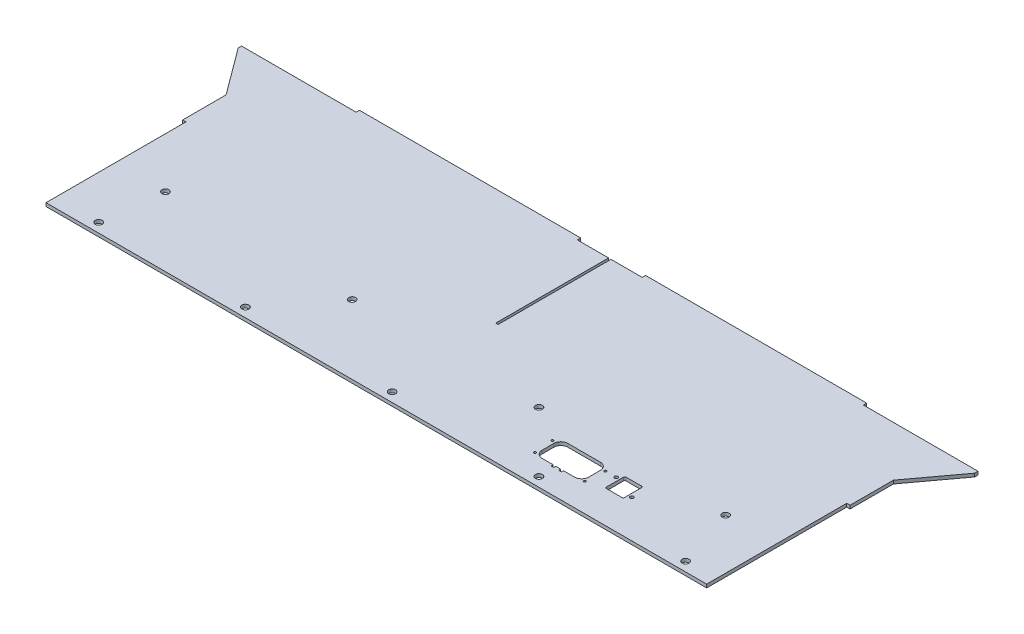
SolidWorks part; units mm, degrees
material "6061-T6 (SS)"
ref_plane "X-Y Datum" through (0, 0, 0) normal (0, 0, 1) x (1, 0, 0)
ref_plane "X-Z Datum" through (0, 0, 0) normal (0, 1, 0) x (1, 0, 0)
ref_plane "Y-Z Datum" through (0, 0, 0) normal (1, 0, 0) x (0, 0, -1)
sketch "Sketch1" plane through (0, 0, 0) normal (0, 1, 0) x (1, 0, 0)
  line L1 (-317.6778, 111.125) -> (317.6778, 111.125)
  line L2 (-317.6778, 111.125) -> (-317.6778, -111.125)
  line L3 (-317.6778, -111.125) -> (317.6778, -111.125)
  line L4 (317.6778, 111.125) -> (317.6778, -111.125)
  line L5 (-317.6778, 111.125) -> (317.6778, -111.125) construction
  line L6 (-317.6778, -111.125) -> (317.6778, 111.125) construction
  point P0 (0, 0)
  dimension "D1" = 635.3556
  dimension "D2" = 222.25
extrude "Boss-Extrude1" add sketch "Sketch1" along normal mid plane 3.175
sketch "Sketch3" plane through (0, 1.5875, 0) normal (0, 1, 0) x (1, 0, 0)
  line L0 (-317.6778, 111.125) -> (-350.5784, 111.125)
  line L1 (-350.5784, 111.125) -> (-350.5784, 107.95)
  line L2 (-350.5784, 107.95) -> (-317.6778, 63.5)
  line L3 (-317.6778, 111.125) -> (-317.6778, -111.125) construction
  line L16 (317.6778, -111.125) -> (317.6778, 111.125)
  line L17 (317.6778, 111.125) -> (-317.6778, 111.125)
  line L26 (-317.6778, 111.125) -> (-317.6778, -111.125)
  line L27 (-317.6778, -111.125) -> (317.6778, -111.125)
  line L38 (-317.6778, 111.125) -> (-317.6778, 63.5)
  line M26 (-317.6778, 111.125) -> (-317.6778, -111.125)
  dimension "D1" = 32.9006
  dimension "D2" = 3.175
  dimension "D3" = 44.45
  dimension "D4" = 0
extrude "Boss-Extrude3" add sketch "Sketch3" against normal blind 3.175 contours L1 L2 L0 M26
mirror "Mirror1" about plane through (0, 0, 0) normal (1, 0, 0) of "Boss-Extrude3"
sketch "Sketch4" plane through (0, 1.5875, 0) normal (0, 1, 0) x (1, 0, 0)
  line L0 (-273.2278, -111.125) -> (-273.2278, -102.235)
  line L1 (-317.6778, -111.125) -> (317.6778, -111.125) construction
  line L2 (-273.2278, -102.235) -> (-317.6778, -102.235)
  line L3 (-317.6778, 63.5) -> (-317.6778, -111.125) construction
  circle A0 centre (-273.2278, -102.235) radius 3.302
  dimension "D1" = 6.604
extrude "Cut-Extrude1" cut sketch "Sketch4" against normal blind 10 contours L0 A0 L2 | L2 A0 L0
pattern_linear "LPattern1" count 5 spacing 139.7 along (1, 0, 0) of "Cut-Extrude1"
sketch "Sketch6" plane through (0, 1.5875, 0) normal (0, 1, 0) x (1, 0, 0)
  line L0 (0, -191.7444) -> (0, 191.7444) construction
  line L1 (317.6778, -111.125) -> (314.5028, -111.125)
  line L2 (317.6778, -111.125) -> (317.6778, 22.225)
  line L3 (317.6778, 22.225) -> (314.5028, 22.225)
  line L4 (314.5028, -111.125) -> (314.5028, 22.225)
  line L5 (-317.6778, -111.125) -> (-314.5028, -111.125)
  line L6 (-317.6778, 22.225) -> (-314.5028, 22.225)
  line L7 (-317.6778, -111.125) -> (-317.6778, 22.225)
  line L8 (-314.5028, -111.125) -> (-314.5028, 22.225)
  line L9 (350.5784, 111.125) -> (-350.5784, 111.125) construction
  line L10 (1.143, 111.125) -> (-1.143, 111.125)
  line L11 (1.143, 111.125) -> (1.143, 3.683)
  line L12 (1.143, 3.683) -> (-1.143, 3.683)
  line L13 (-1.143, 111.125) -> (-1.143, 3.683)
  line L14 (0, 3.683) -> (0, 111.125) construction
  point P9 (0, 0)
  dimension "D1" = 3.175
  dimension "D2" = 133.35
  dimension "D3" = 107.442
  dimension "D4" = 2.286
extrude "Cut-Extrude2" cut sketch "Sketch6" against normal through all
sketch "Sketch8" plane through (0, 1.5875, 0) normal (0, 1, 0) x (1, 0, 0)
  line L0 (-314.5028, -111.125) -> (314.5028, -111.125) construction
  line L1 (314.5028, 22.225) -> (314.5028, -111.125) construction
  circle A0 centre (266.7, -45.2374) radius 3
  dimension "D3" = 6
  dimension "D1" = 65.8876
  dimension "D2" = 47.8028
hole_wizard "M6 Clearance Hole1" positions "Sketch9" profile "Sketch10" hole size "M6" standard "ANSI Metric" end condition through all
sketch "Sketch9" plane through (0, 1.5875, 0) normal (0, 1, 0) x (1, 0, 0)
  point P0 (266.7, -45.2374)
sketch "Sketch10" plane through (266.7, 1.5875, 45.2374) normal (1, 0, 0) x (0, 0, 1)
  line L0 (0, 0) -> (0, 3.175)
  line L1 (0, 3.175) -> (3.3, 3.175)
  line L2 (3.3, 3.175) -> (3.3, 0)
  line L5 (3.3, 0) -> (0, 0)
  line L11 (0, -6.35) -> (0, 107.95) construction
  dimension "Thru Hole Dia." = 6.6
  dimension "Thru Hole Depth" = 3.175
pattern_linear "LPattern2" count 4 spacing 177.8 along (-1, 0, 0) of "M6 Clearance Hole1"
sketch "Sketch12" plane through (0, 0, -111.125) normal (0, 0, -1) x (-1, 0, 0)
  line L0 (-350.5784, -1.5875) -> (-1.143, -1.5875) construction
  line L1 (-241.4778, -1.5875) -> (-30.8229, -1.5875)
  line L2 (-241.4778, -1.5875) -> (-241.4778, 1.5875)
  line L3 (-241.4778, 1.5875) -> (-30.8229, 1.5875)
  line L4 (-30.8229, -1.5875) -> (-30.8229, 1.5875)
  line L5 (-241.4778, -1.5875) -> (-241.4778, 1.5875) construction
  line L6 (-350.5784, 1.5875) -> (-1.143, 1.5875) construction
  line L7 (-30.8229, 1.5875) -> (-30.8229, -1.5875) construction
  line L8 (1.143, 1.5875) -> (350.5784, 1.5875) construction
  line L9 (30.8229, 1.5875) -> (241.4778, 1.5875)
  line L10 (30.8229, 1.5875) -> (30.8229, -1.5875)
  line L11 (30.8229, -1.5875) -> (241.4778, -1.5875)
  line L12 (241.4778, 1.5875) -> (241.4778, -1.5875)
  line L13 (30.8229, 1.5875) -> (30.8229, -1.5875) construction
  line L14 (1.143, -1.5875) -> (350.5784, -1.5875) construction
  line L15 (241.4778, -1.5875) -> (241.4778, 1.5875) construction
extrude "Boss-Extrude4" add sketch "Sketch12" along normal blind 3.175
sketch "Sketch13" plane through (0, 1.5875, 0) normal (0, 1, 0) x (1, 0, 0)
  line L1 (145.2142, -85.2806) -> (143.4142, -85.2806) construction
  line L4 (152.4142, -85.2806) -> (150.6142, -85.2806) construction
  line L12 (145.4974, -87.7806) -> (145.7599, -84.7806) construction
  line L21 (143.131, -87.7806) -> (145.4974, -87.7806) construction
  line L22 (187.8642, -80.0254) -> (202.8142, -80.0254)
  line L23 (203.9642, -78.8754) -> (203.9642, -62.4254)
  line L28 (202.8142, -61.2754) -> (187.8642, -61.2754)
  line L29 (186.7142, -62.4254) -> (186.7142, -78.8754)
  line L30 (187.8642, -80.0254) -> (202.8142, -80.0254)
  line L45 (203.9642, -78.8754) -> (203.9642, -62.4254)
  line L46 (202.8142, -61.2754) -> (187.8642, -61.2754)
  line L47 (186.7142, -62.4254) -> (186.7142, -78.8754)
  line L60 (142.8686, -84.7806) -> (143.131, -87.7806) construction
  line L62 (152.4142, -85.7806) -> (163.4142, -85.7806) construction
  line L72 (170.1142, -79.0806) -> (170.1142, -67.8806) construction
  line L241 (163.4142, -61.1806) -> (132.4142, -61.1806) construction
  line L242 (125.7142, -67.8806) -> (125.7142, -79.0806) construction
  line L243 (132.4142, -85.7806) -> (143.4142, -85.7806) construction
  line L244 (202.8142, -79.5254) -> (202.8142, -78.8754) construction
  line L245 (152.6974, -87.7806) -> (152.9599, -84.7806) construction
  line L246 (150.331, -87.7806) -> (152.6974, -87.7806) construction
  line L247 (150.0686, -84.7806) -> (150.331, -87.7806) construction
  line L248 (145.2142, -85.7806) -> (150.6142, -85.7806) construction
  line L249 (145.2142, -85.2806) -> (143.4142, -85.2806)
  line L250 (152.4142, -85.2806) -> (150.6142, -85.2806)
  line L251 (145.4974, -87.7806) -> (145.7599, -84.7806)
  line L252 (143.131, -87.7806) -> (145.4974, -87.7806)
  line L253 (142.8686, -84.7806) -> (143.131, -87.7806)
  line L254 (152.4142, -85.7806) -> (163.4142, -85.7806)
  line L255 (170.1142, -79.0806) -> (170.1142, -67.8806)
  line L256 (163.4142, -61.1806) -> (132.4142, -61.1806)
  line L257 (125.7142, -67.8806) -> (125.7142, -79.0806)
  line L258 (132.4142, -85.7806) -> (143.4142, -85.7806)
  line L259 (202.8142, -79.5254) -> (202.8142, -78.8754)
  line L260 (152.6974, -87.7806) -> (152.9599, -84.7806)
  line L261 (150.331, -87.7806) -> (152.6974, -87.7806)
  line L262 (150.0686, -84.7806) -> (150.331, -87.7806)
  line L263 (145.2142, -85.7806) -> (150.6142, -85.7806)
  arc A72 (163.4142, -85.7806) -> (170.1142, -79.0806) centre (163.4142, -79.0806) ccw construction
  arc A73 (170.1142, -67.8806) -> (163.4142, -61.1806) centre (163.4142, -67.8806) ccw construction
  arc A74 (132.4142, -61.1806) -> (125.7142, -67.8806) centre (132.4142, -67.8806) ccw construction
  arc A75 (125.7142, -79.0806) -> (132.4142, -85.7806) centre (132.4142, -79.0806) ccw construction
  arc A76 (163.4142, -85.7806) -> (170.1142, -79.0806) centre (163.4142, -79.0806) ccw
  arc A77 (170.1142, -67.8806) -> (163.4142, -61.1806) centre (163.4142, -67.8806) ccw
  arc A78 (132.4142, -61.1806) -> (125.7142, -67.8806) centre (132.4142, -67.8806) ccw
  arc A79 (125.7142, -79.0806) -> (132.4142, -85.7806) centre (132.4142, -79.0806) ccw
  spline S8 degree 3 poles (-1181.2105, -3830.7355) (169.3547, 150.7576) (191.288, -87.5436) (203.6527, -79.7139) (211.4824, -67.3492) (-26.8186, -45.4159) (3954.6692, 1305.1476) knots -21.653604 -21.653604 -21.653604 -21.653604 0.25 0.5 0.75 22.653594 22.653594 22.653594 22.653594 only from (202.8142, -80.0254) to (203.9642, -78.8754)
  spline S9 degree 3 poles (3954.6744, -1446.4502) (-26.8188, -95.8849) (211.4824, -73.9516) (203.6527, -61.5869) (191.288, -53.7572) (169.3547, -292.0582) (-1181.2088, 3689.4295) knots -21.653604 -21.653604 -21.653604 -21.653604 0.25 0.5 0.75 22.653594 22.653594 22.653594 22.653594 only from (203.9642, -62.4254) to (202.8142, -61.2754)
  spline S10 degree 3 poles (1571.889, 3689.4347) (221.3238, -292.0584) (199.3905, -53.7572) (187.0258, -61.5869) (179.196, -73.9516) (417.497, -95.8849) (-3563.9907, -1446.4484) knots -21.653604 -21.653604 -21.653604 -21.653604 0.25 0.5 0.75 22.653594 22.653594 22.653594 22.653594 only from (187.8642, -61.2754) to (186.7142, -62.4254)
  spline S11 degree 3 poles (-3563.9959, 1305.1494) (417.4973, -45.4159) (179.196, -67.3492) (187.0258, -79.7139) (199.3905, -87.5436) (221.3237, 150.7574) (1571.8872, -3830.7303) knots -21.653604 -21.653604 -21.653604 -21.653604 0.25 0.5 0.75 22.653594 22.653594 22.653594 22.653594 only from (186.7142, -78.8754) to (187.8642, -80.0254)
  spline S28 degree 3 poles (202.8142, -80.0254) (202.9579, -80.0254) (203.2388, -79.976) (203.6527, -79.7139) (203.9148, -79.2999) (203.9642, -79.019) (203.9642, -78.8754) knots 0 0 0 0 0.25 0.5 0.75 1 1 1 1
  spline S29 degree 3 poles (203.9642, -62.4254) (203.9642, -62.2817) (203.9148, -62.0009) (203.6527, -61.5869) (203.2388, -61.3248) (202.9579, -61.2754) (202.8142, -61.2754) knots 0 0 0 0 0.25 0.5 0.75 1 1 1 1
  spline S30 degree 3 poles (187.8642, -61.2754) (187.7206, -61.2754) (187.4397, -61.3248) (187.0258, -61.5869) (186.7636, -62.0009) (186.7142, -62.2817) (186.7142, -62.4254) knots 0 0 0 0 0.25 0.5 0.75 1 1 1 1
  spline S31 degree 3 poles (186.7142, -78.8754) (186.7142, -79.019) (186.7636, -79.2999) (187.0258, -79.7139) (187.4397, -79.976) (187.7206, -80.0254) (187.8642, -80.0254) knots 0 0 0 0 0.25 0.5 0.75 1 1 1 1
  spline S140 degree 3 poles (172.6992, -84.2806) (172.6992, -86.4506) (170.5292, -86.4506) (170.5292, -84.2806) knots 0 0 0 0 1 1 1 1 weights 1 0.333333 0.333333 1 construction
  spline S141 degree 3 poles (170.5292, -84.2806) (170.5292, -82.1106) (172.6992, -82.1106) (172.6992, -84.2806) knots 0 0 0 0 1 1 1 1 weights 1 0.333333 0.333333 1 construction
  spline S142 degree 3 poles (121.6292, -66.1806) (121.6292, -64.0106) (123.7992, -64.0106) (123.7992, -66.1806) knots 0 0 0 0 1 1 1 1 weights 1 0.333333 0.333333 1 construction
  spline S143 degree 3 poles (123.7992, -66.1806) (123.7992, -68.3506) (121.6292, -68.3506) (121.6292, -66.1806) knots 0 0 0 0 1 1 1 1 weights 1 0.333333 0.333333 1 construction
  spline S144 degree 3 poles (123.1292, -84.2806) (123.1292, -82.1106) (125.2992, -82.1106) (125.2992, -84.2806) knots 0 0 0 0 1 1 1 1 weights 1 0.333333 0.333333 1 construction
  spline S145 degree 3 poles (125.2992, -84.2806) (125.2992, -86.4506) (123.1292, -86.4506) (123.1292, -84.2806) knots 0 0 0 0 1 1 1 1 weights 1 0.333333 0.333333 1 construction
  spline S146 degree 3 poles (172.6992, -84.2806) (172.6992, -86.4506) (170.5292, -86.4506) (170.5292, -84.2806) knots 0 0 0 0 1 1 1 1 weights 1 0.333333 0.333333 1
  spline S147 degree 3 poles (170.5292, -84.2806) (170.5292, -82.1106) (172.6992, -82.1106) (172.6992, -84.2806) knots 0 0 0 0 1 1 1 1 weights 1 0.333333 0.333333 1
  spline S148 degree 3 poles (121.6292, -66.1806) (121.6292, -64.0106) (123.7992, -64.0106) (123.7992, -66.1806) knots 0 0 0 0 1 1 1 1 weights 1 0.333333 0.333333 1
  spline S149 degree 3 poles (123.7992, -66.1806) (123.7992, -68.3506) (121.6292, -68.3506) (121.6292, -66.1806) knots 0 0 0 0 1 1 1 1 weights 1 0.333333 0.333333 1
  spline S150 degree 3 poles (123.1292, -84.2806) (123.1292, -82.1106) (125.2992, -82.1106) (125.2992, -84.2806) knots 0 0 0 0 1 1 1 1 weights 1 0.333333 0.333333 1
  spline S151 degree 3 poles (125.2992, -84.2806) (125.2992, -86.4506) (123.1292, -86.4506) (123.1292, -84.2806) knots 0 0 0 0 1 1 1 1 weights 1 0.333333 0.333333 1
  spline S152 degree 3 poles (172.0292, -66.1806) (172.0292, -64.0106) (174.1992, -64.0106) (174.1992, -66.1806) knots 0 0 0 0 1 1 1 1 weights 1 0.333333 0.333333 1 construction
  spline S153 degree 3 poles (174.1992, -66.1806) (174.1992, -68.3506) (172.0292, -68.3506) (172.0292, -66.1806) knots 0 0 0 0 1 1 1 1 weights 1 0.333333 0.333333 1 construction
  spline S154 degree 3 poles (172.0292, -66.1806) (172.0292, -64.0106) (174.1992, -64.0106) (174.1992, -66.1806) knots 0 0 0 0 1 1 1 1 weights 1 0.333333 0.333333 1
  spline S155 degree 3 poles (174.1992, -66.1806) (174.1992, -68.3506) (172.0292, -68.3506) (172.0292, -66.1806) knots 0 0 0 0 1 1 1 1 weights 1 0.333333 0.333333 1
  spline S156 degree 3 poles (181.7392, -66.1504) (181.7392, -69.3504) (184.9392, -69.3504) (184.9392, -66.1504) (184.9392, -62.9504) (181.7392, -62.9504) (181.7392, -66.1504) (181.7392, -69.3504) (184.9392, -69.3504) knots -0.5 0 0 0 0.5 0.5 0.5 1 1 1 1.5 1.5 1.5 weights 1 0.333333 0.333333 1 0.333333 0.333333 1 0.333333 0.333333 only from (181.7392, -66.1504) to (181.7392, -66.1504) construction
  spline S157 degree 3 poles (205.7392, -75.1504) (205.7392, -78.3504) (208.9392, -78.3504) (208.9392, -75.1504) (208.9392, -71.9504) (205.7392, -71.9504) (205.7392, -75.1504) (205.7392, -78.3504) (208.9392, -78.3504) knots -0.5 0 0 0 0.5 0.5 0.5 1 1 1 1.5 1.5 1.5 weights 1 0.333333 0.333333 1 0.333333 0.333333 1 0.333333 0.333333 only from (205.7392, -75.1504) to (205.7392, -75.1504) construction
  spline S158 degree 3 poles (181.7392, -66.1504) (181.7392, -69.3504) (184.9392, -69.3504) (184.9392, -66.1504) (184.9392, -62.9504) (181.7392, -62.9504) (181.7392, -66.1504) (181.7392, -69.3504) (184.9392, -69.3504) knots -0.5 0 0 0 0.5 0.5 0.5 1 1 1 1.5 1.5 1.5 weights 1 0.333333 0.333333 1 0.333333 0.333333 1 0.333333 0.333333 only from (181.7392, -66.1504) to (181.7392, -66.1504)
  spline S159 degree 3 poles (205.7392, -75.1504) (205.7392, -78.3504) (208.9392, -78.3504) (208.9392, -75.1504) (208.9392, -71.9504) (205.7392, -71.9504) (205.7392, -75.1504) (205.7392, -78.3504) (208.9392, -78.3504) knots -0.5 0 0 0 0.5 0.5 0.5 1 1 1 1.5 1.5 1.5 weights 1 0.333333 0.333333 1 0.333333 0.333333 1 0.333333 0.333333 only from (205.7392, -75.1504) to (205.7392, -75.1504)
  dimension "D1" = 0
extrude "Cut-Extrude3" cut sketch "Sketch13" against normal through all
